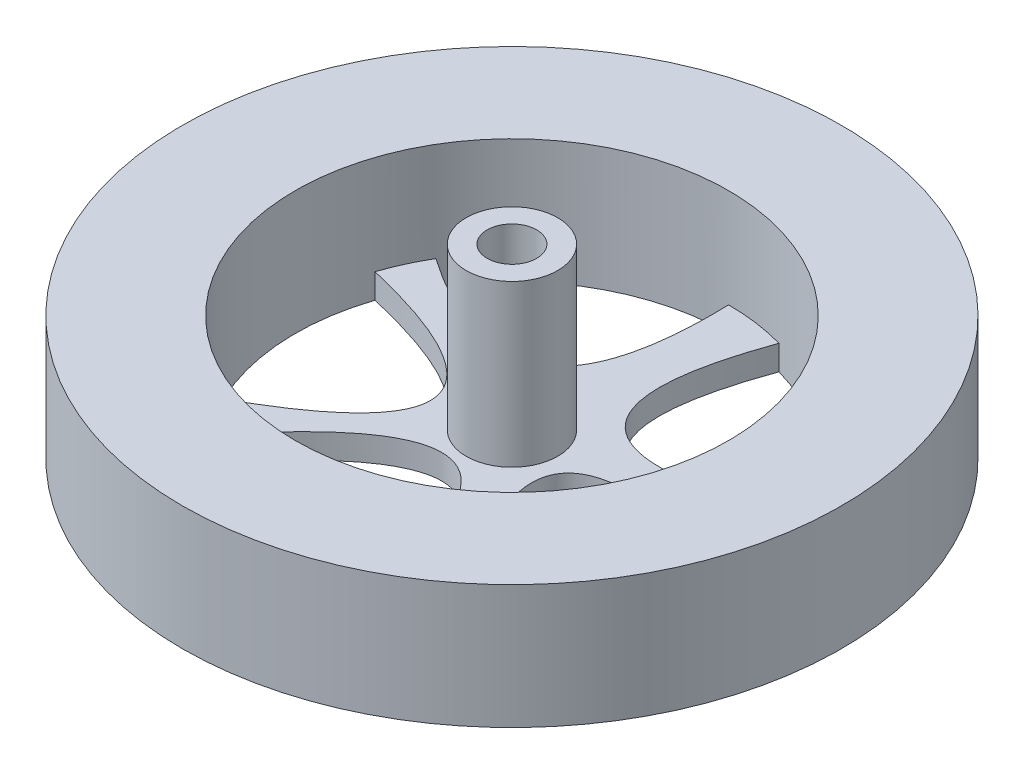
SolidWorks part; units mm, degrees
ref_plane "Front Plane" through (0, 0, 0) normal (0, 0, 1) x (1, 0, 0)
ref_plane "Top Plane" through (0, 0, 0) normal (0, 1, 0) x (1, 0, 0)
ref_plane "Right Plane" through (0, 0, 0) normal (1, 0, 0) x (0, 0, -1)
sketch "Sketch3" plane through (0, 0, 0) normal (0, 1, 0) x (1, 0, 0)
  circle A0 centre (0, 0) radius 31.75
  dimension "D1" = 63.5
extrude "Boss-Extrude1" add sketch "Sketch3" along normal blind 12.7 contours A0
sketch "Sketch4" plane through (0, 12.7, 0) normal (0, 1, 0) x (1, 0, 0)
  circle A0 centre (0, 0) radius 22.225
  dimension "D1" = 44.45
extrude "Cut-Extrude1" cut sketch "Sketch4" against normal blind 10.16
sketch "Sketch7" plane through (0, 2.54, 0) normal (0, 1, 0) x (1, 0, 0)
  circle A0 centre (0, 0) radius 22.225 construction
  circle A1 centre (0, 0) radius 22.225
  arc A2 (-15.2294, -16.1869) -> (6.5488, -21.2383) centre (0, 0) ccw
  circle A3 centre (0, 0) radius 22.225 construction
  arc A4 (13.0506, -17.9898) -> (22.1964, -1.1279) centre (0, 0) ccw
  arc A5 (21.2549, 6.4946) -> (5.9976, 21.4005) centre (0, 0) ccw
  arc A6 (0, 22.225) -> (-19.1251, 11.3217) centre (0, 0) ccw
  arc A7 (-21.08, 7.0416) -> (-18.3725, -12.506) centre (0, 0) ccw
  spline S0 degree 2 poles (0, 22.225) (0.7336, -2.4193) (-19.1251, 11.3217) knots 0 0 0 1 1 1
  spline S1 degree 2 poles (-21.08, 7.0416) (6.0675, 0.6079) (-18.3725, -12.506) knots 0 0 0 1 1 1
  spline S2 degree 2 poles (-15.2294, -16.1869) (3.3075, 7.2596) (6.5488, -21.2383) knots 0 0 0 1 1 1
  spline S3 degree 2 poles (13.0506, -17.9898) (-5.3019, 6.172) (22.1964, -1.1279) knots 0 0 0 1 1 1
  spline S4 degree 2 poles (5.9976, 21.4005) (-2.4247, -1.9073) (21.2549, 6.4946) knots 0 0 0 1 1 1
  point P17 (-4.6669, 7.0416)
  point P19 (-6.8209, -1.1279)
  point P20 (0, -5.8785)
  point P21 (6.5488, -1.1279)
  point P22 (5.4747, 6.1478)
  point P23 (5.9976, 21.4005)
  point P26 (0, 22.225)
  dimension "D1" = 0
extrude "Cut-Extrude2" cut sketch "Sketch7" against normal blind 10.16
sketch "Sketch8" plane through (0, 2.54, 0) normal (0, 1, 0) x (1, 0, 0)
  circle A0 centre (0, 0) radius 4.6948
extrude "Boss-Extrude2" add sketch "Sketch8" along normal blind 16.51
sketch "Sketch9" plane through (0, 19.05, 0) normal (0, 1, 0) x (1, 0, 0)
  circle A0 centre (0, 0) radius 2.54
extrude "Cut-Extrude3" cut sketch "Sketch9" against normal blind 10.16
sketch "Sketch10" plane through (0, 0, 0) normal (0, 0, 1) x (1, 0, 0)
  line L0 (-31.75, 12.7) -> (-33.8154, 12.7)
  line L1 (-33.8154, 12.7) -> (-33.8154, 0)
  line L2 (-33.8154, 0) -> (-31.75, 0)
  line L3 (-31.75, 0) -> (-31.75, 12.7)
  line L4 (0, 24.1379) -> (0, -4.567) construction
revolve "Revolve1" add sketch "Sketch10" angle 360 about L4
